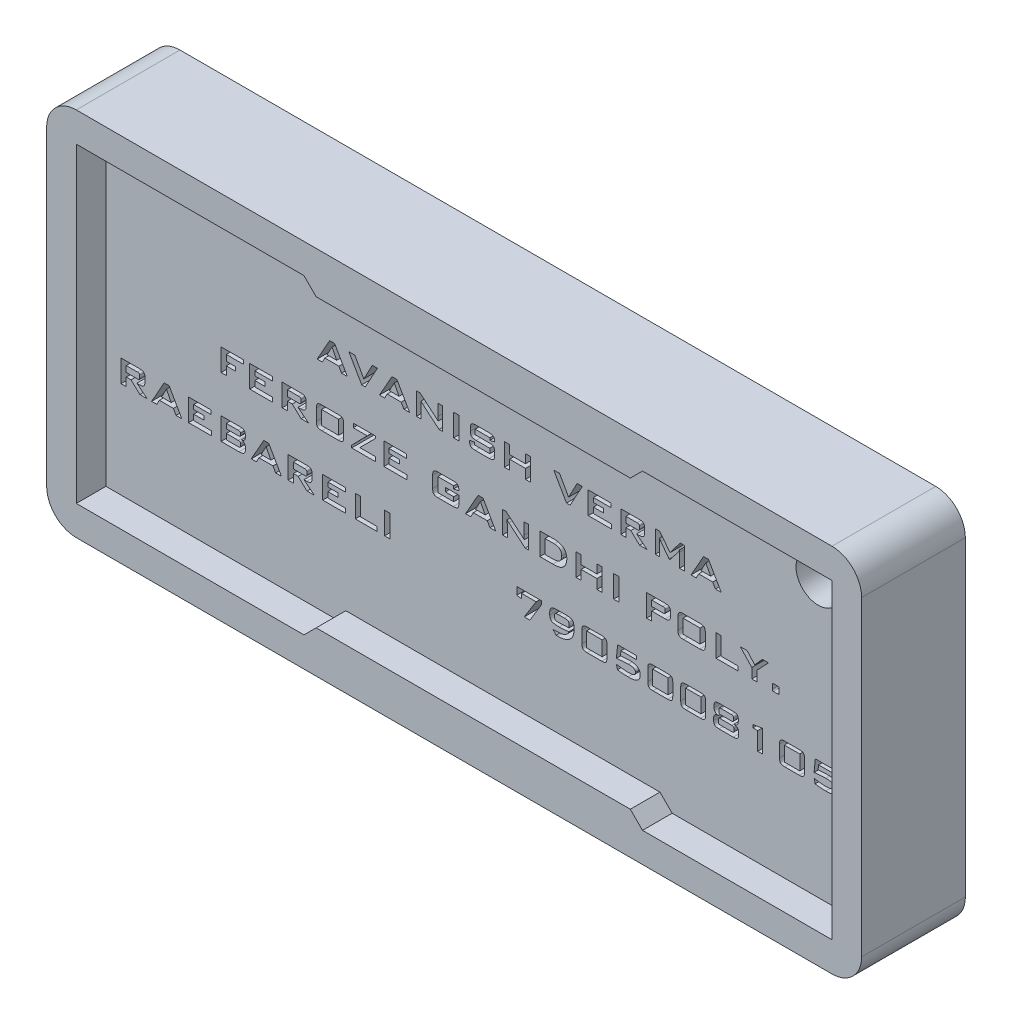
SolidWorks part; units mm, degrees
ref_plane "Front Plane" through (0, 0, 0) normal (0, 0, 1) x (1, 0, 0)
ref_plane "Top Plane" through (0, 0, 0) normal (0, 1, 0) x (1, 0, 0)
ref_plane "Right Plane" through (0, 0, 0) normal (1, 0, 0) x (0, 0, -1)
sketch "Sketch1" plane through (0, 0, 0) normal (0, 0, 1) x (1, 0, 0)
  line L1 (-25.5, -12.5) -> (25.5, -12.5)
  line L2 (-27.5, -10.5) -> (-27.5, 10.5)
  line L3 (-25.5, 12.5) -> (25.5, 12.5)
  line L4 (27.5, -10.5) -> (27.5, 10.5)
  line L5 (-27.5, -12.5) -> (27.5, 12.5) construction
  line L6 (-27.5, 12.5) -> (27.5, -12.5) construction
  arc A0 (-25.5, -12.5) -> (-27.5, -10.5) centre (-25.5, -10.5) cw
  arc A1 (27.5, -10.5) -> (25.5, -12.5) centre (25.5, -10.5) cw
  arc A2 (27.5, 10.5) -> (25.5, 12.5) centre (25.5, 10.5) ccw
  arc A3 (-25.5, 12.5) -> (-27.5, 10.5) centre (-25.5, 10.5) ccw
  point P0 (0, 0)
  dimension "D3" = 2
  dimension "D1" = 55
  dimension "D2" = 25
extrude "Boss-Extrude1" add sketch "Sketch1" along normal blind 7
sketch "Sketch2" plane through (0, 0, 0) normal (0, 0, -1) x (-1, 0, 0)
  line L0 (-27.5, -10.5) -> (-27.5, 10.5) construction
  line L1 (-25.5, -10.5) -> (-11.552, -10.5)
  line L2 (-25.5, -10.5) -> (-25.5, 10.5)
  line L3 (-25.5, 10.5) -> (-11.552, 10.5)
  line L4 (25.5, -10.5) -> (25.5, 10.5)
  line L5 (-25.5, -10.5) -> (-23.5, -9.6765) construction
  line L6 (-25.5, 10.5) -> (-23.5, 9.6765) construction
  line L7 (-25.5, 12.5) -> (25.5, 12.5) construction
  line L8 (-11.552, 10.5) -> (-10.7284, 9.6765)
  line L13 (-23.5, -9.6765) -> (0, 0) construction
  line L14 (10.0955, 10.5) -> (25.5, 10.5)
  line L15 (-11.552, 10.5) -> (-25.5, 10.5)
  line L16 (9.272, 9.6765) -> (10.0955, 10.5)
  line L17 (-11.552, -10.5) -> (-10.7284, -9.6765)
  line L18 (10.0955, -10.5) -> (25.5, -10.5)
  line L19 (9.272, -9.6765) -> (10.0955, -10.5)
  line L20 (-11.552, -10.5) -> (-25.5, -10.5)
  line L22 (10.0955, -10.5) -> (9.272, -9.6765)
  line L23 (25.5, -10.5) -> (10.0955, -10.5)
  line L24 (25.5, -10.5) -> (25.5, 10.5)
  line L25 (25.5, 10.5) -> (10.0955, 10.5)
  line L26 (-25.5, -10.5) -> (-25.5, 10.5)
  line L27 (23.5, -9.6765) -> (-25.5, 10.5) construction
  line L28 (25.5, 10.5) -> (-25.5, -10.5) construction
  line L29 (9.272, -9.6765) -> (-10.7284, -9.6765)
  line L31 (9.272, 9.6765) -> (-10.7284, 9.6765)
  line L33 (23.5, -9.6765) -> (-23.5, 9.6765) construction
  line L34 (23.5, 9.6765) -> (-23.5, -9.6765) construction
  line L35 (-10.7284, -9.6765) -> (-11.552, -10.5)
  line L36 (10.0955, 10.5) -> (9.272, 9.6765)
  line L37 (-10.7284, 9.6765) -> (-11.552, 10.5)
  point P0 (0, 0)
  point P10 (0, 0)
  dimension "D1" = 2
  dimension "D2" = 2
extrude "Cut-Extrude1" cut sketch "Sketch2" against normal blind 2 contours L16 L31 L8 L3 L2 L1 L17 L29 L19 L18 L4 L14
sketch "Sketch3" plane through (0, 0, 7) normal (0, 0, 1) x (1, 0, 0)
  line L0 (-27.5, 10.5) -> (-27.5, -10.5) construction
  line L1 (-25.5, -10.5) -> (-10.1359, -10.5)
  line L2 (-25.5, -10.5) -> (-25.5, 10.5)
  line L3 (-25.5, 10.5) -> (-10.1359, 10.5)
  line L4 (25.5, -10.5) -> (25.5, 10.5)
  line L5 (-25.5, -10.5) -> (-23.5, -9.6765) construction
  line L6 (-25.5, 10.5) -> (-23.5, 9.6765) construction
  line L7 (25.5, 12.5) -> (-25.5, 12.5) construction
  line L8 (-10.1359, 10.5) -> (-9.3123, 9.6765)
  line L9 (-9.3123, -9.6765) -> (11.8893, -9.6765)
  line L13 (-23.5, -9.6765) -> (0, 0) construction
  line L14 (-23.5, 9.6765) -> (0, 0) construction
  line L17 (12.7129, 10.5) -> (11.8893, 9.6765)
  line L18 (12.7129, 10.5) -> (25.5, 10.5)
  line L19 (-10.1359, -10.5) -> (-9.3123, -9.6765)
  line L20 (-9.3123, -9.6765) -> (11.8893, -9.6765)
  line L21 (11.8893, -9.6765) -> (12.7129, -10.5)
  line L22 (-9.3123, 9.6765) -> (11.8893, 9.6765)
  line L23 (0, 0) -> (25.5, -10.5) construction
  line L24 (0, 0) -> (25.5, 10.5) construction
  line L25 (12.7129, -10.5) -> (25.5, -10.5)
  point P0 (0, 0)
  point P10 (0, 0)
  dimension "D1" = 2
  dimension "D2" = 2
extrude "Cut-Extrude2" cut sketch "Sketch3" against normal blind 2 contours L21 L25 L4 L18 L17 L22 L8 L3 L2 L1 L19 L9
sketch "Sketch4" plane through (0, 0, 5) normal (0, 0, 1) x (1, 0, 0)
  text T0 "            AVANISH VERMA\r\n      FEROZE GANDHI POLY.\r\nRAEBARELI       7905008105" font "BankGothic Md BT" height 1.5
extrude "Cut-Extrude10" cut sketch "Sketch4" against normal blind 3
sketch "Sketch5" plane through (0, 0, 5) normal (0, 0, 1) x (1, 0, 0)
  circle A0 centre (22.5719, 8.0869) radius 1.5
extrude "Cut-Extrude11" cut sketch "Sketch5" against normal blind 3
